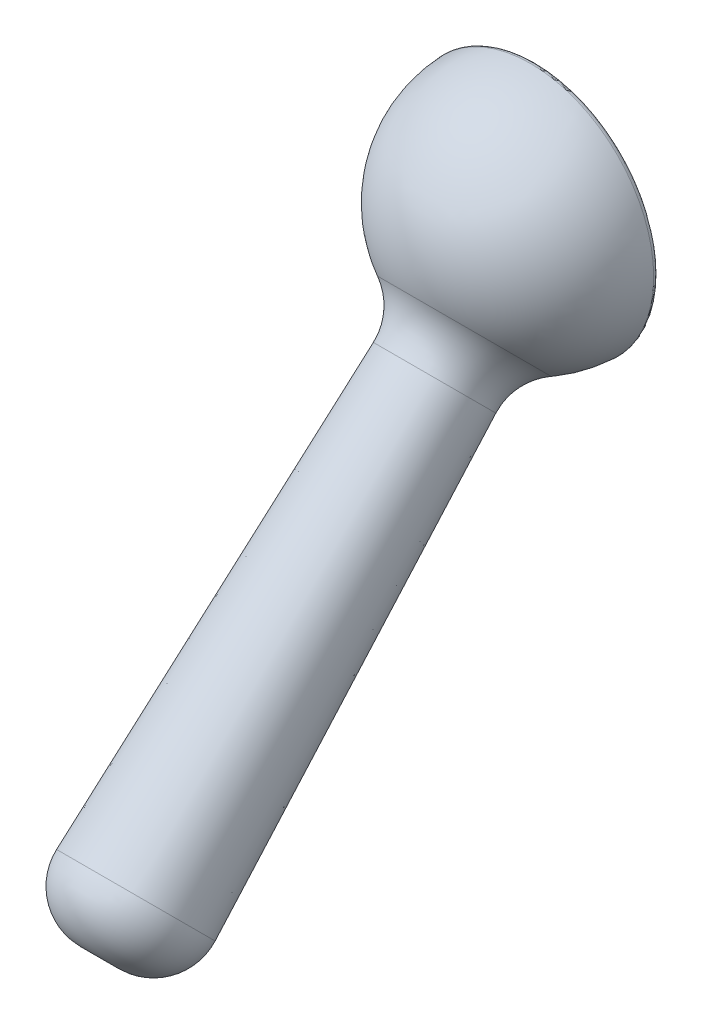
SolidWorks part; units mm, degrees
ref_plane "Front Plane" through (0, 0, 0) normal (1, 0, 0) x (0, 1, 0)
ref_plane "Top Plane" through (0, 0, 0) normal (0, 0, 1) x (0, 1, 0)
ref_plane "Right Plane" through (0, 0, 0) normal (0, 1, 0) x (-1, 0, 0)
sketch "Sketch1" plane through (0, 0, 0) normal (1, 0, 0) x (0, 1, 0)
  line L0 (0, 25) -> (0, 20)
  line L1 (20, 0) -> (25, 0)
  arc A0 (20, 0) -> (0, 20) centre (0, 0) ccw
  arc A1 (25, 0) -> (0, 25) centre (0, 0) ccw
  dimension "D1" = 40
  dimension "D2" = 50
revolve "Revolve1" add sketch "Sketch1" angle 360 about L0
sketch "Sketch2" plane through (0, 0, 0) normal (1, 0, 0) x (0, 1, 0)
  line L0 (0, 0) -> (-17.6777, 17.6777) construction
  line L1 (-25, 0) -> (25, 0) construction
  arc A0 (25, 0) -> (-25, 0) centre (0, 0) ccw construction
  dimension "D1" = 45
ref_plane "Plane1" through (0, -17.6777, 17.6777) normal (0, -0.7071, 0.7071) x (-1, 0, 0)
sketch "Sketch3" plane through (0, -17.6777, 17.6777) normal (0, -0.7071, 0.7071) x (-1, 0, 0)
  circle A0 centre (0, 0) radius 10
  dimension "D1" = 20
extrude "Boss-Extrude1" add sketch "Sketch3" along normal blind 100 draft 2 and the other way blind 2.5 draft 2 other way draft outward yes draft outward yes
fillet "Fillet1" radius 10 1 edges at (0, -97.9287, 78.848)
fillet "Fillet2" radius 10 1 edges at (0, -9.0555, 23.3023)
fillet "Fillet3" radius 1 1 edges at (25, 0, 0)
